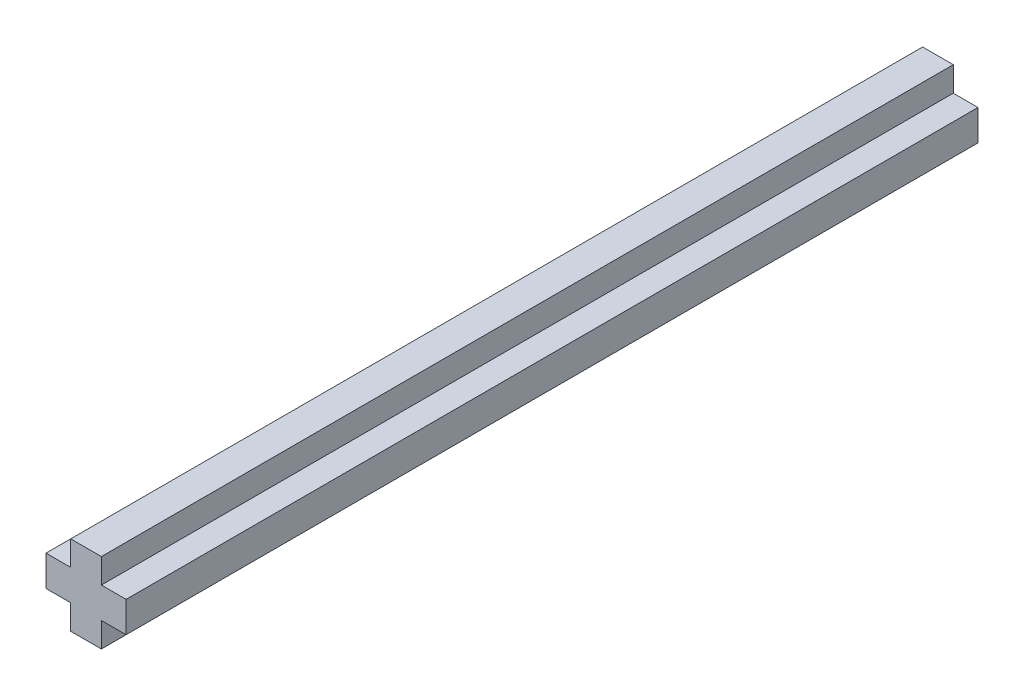
SolidWorks part; units mm, degrees
ref_plane "前视基准面" through (0, 0, 0) normal (0, 0, 1) x (1, 0, 0)
ref_plane "上视基准面" through (0, 0, 0) normal (0, 1, 0) x (1, 0, 0)
ref_plane "右视基准面" through (0, 0, 0) normal (1, 0, 0) x (0, 0, -1)
sketch "草图1" plane through (0, 0, 0) normal (0, 0, 1) x (1, 0, 0)
  line L0 (-0.9, 2.35) -> (-0.9, 0.9)
  line L1 (-0.9, 0.9) -> (-2.35, 0.9)
  line L2 (-2.35, 0.9) -> (-2.35, -0.9)
  line L3 (-2.35, -0.9) -> (-0.9, -0.9)
  line L4 (-0.9, -0.9) -> (-0.9, -2.35)
  line L5 (-0.9, -2.35) -> (0.9, -2.35)
  line L6 (0.9, -2.35) -> (0.9, -0.9)
  line L7 (0.9, -0.9) -> (2.35, -0.9)
  line L8 (2.35, -0.9) -> (2.35, 0.9)
  line L9 (2.35, 0.9) -> (0.9, 0.9)
  line L10 (0.9, 0.9) -> (0.9, 2.35)
  line L11 (0.9, 2.35) -> (-0.9, 2.35)
  line L13 (0, 2.35) -> (0, -2.35) construction
  dimension "D1" = 1.8
  dimension "D2" = 4.7
extrude "凸台-拉伸1" add sketch "草图1" along normal blind 50
